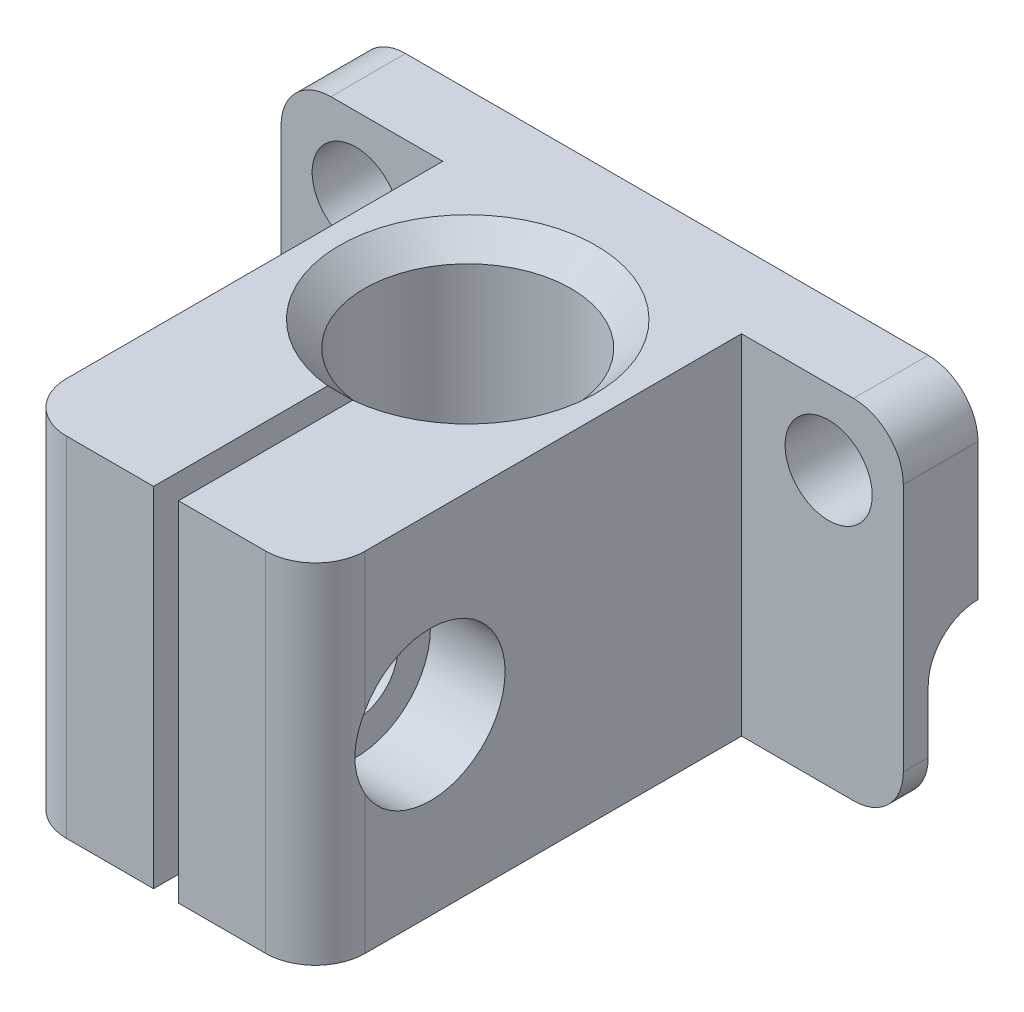
SolidWorks part; units mm, degrees
material "ABS"
ref_plane "Front Plane" through (0, 0, 0) normal (0, 0, 1) x (1, 0, 0)
ref_plane "Top Plane" through (0, 0, 0) normal (0, 1, 0) x (1, 0, 0)
ref_plane "Right Plane" through (0, 0, 0) normal (1, 0, 0) x (0, 0, -1)
sketch "Sketch1" plane through (0, 0, 0) normal (0, 1, 0) x (1, 0, 0)
  line L0 (-12.5, 0) -> (12.5, 0)
  line L1 (12.5, 0) -> (12.5, -3)
  line L2 (12.5, -3) -> (6, -3)
  line L3 (6, -3) -> (6, -20.1198)
  line L4 (6, -20.1198) -> (-6, -20.1198)
  line L5 (-6, -20.1198) -> (-6, -3)
  line L6 (-6, -3) -> (-12.5, -3)
  line L7 (-12.5, -3) -> (-12.5, 0)
  dimension "D1" = 25
  dimension "D2" = 3
  dimension "D3" = 12
  dimension "D4" = 20.1198
extrude "Boss-Extrude1" add sketch "Sketch1" along normal blind 14
sketch "Sketch2" plane through (0, 14, 0) normal (0, 1, 0) x (1, 0, 0)
  line L0 (-0.5, -12.1198) -> (-0.5, -20.1198)
  line L1 (0.5, -12.1198) -> (0.5, -20.1198)
  line L2 (-0.5, -20.1198) -> (0.5, -20.1198)
  line L4 (-6, -20.1198) -> (6, -20.1198) construction
  line L5 (12.5, 0) -> (-12.5, 0) construction
  arc A0 (0.5, -12.1198) -> (-0.5, -12.1198) centre (0, -8) ccw
  dimension "D1" = 1
  dimension "D2" = 8.3
  dimension "D3" = 8
extrude "Cut-Extrude1" cut sketch "Sketch2" against normal through all
chamfer "Chamfer1" distance 1 angle 45 2 edges at (0, 14, 3.85) (0, 0, 3.85)
fillet "Fillet1" radius 2 6 edges at (-12.5, 0, 1.5) (12.5, 0, 1.5) (12.5, 14, 1.5) (-12.5, 14, 1.5) (-6, 7, 20.1198) (6, 7, 20.1198)
sketch "Sketch3" plane through (0, 0, 3) normal (0, 0, 1) x (1, 0, 0)
  line L0 (-10.5, 14) -> (-6, 14) construction
  line L1 (-9.5, 11) -> (9.5, 11) construction
  line L2 (0, 11) -> (0, 14) construction
  line L3 (5.15, 14) -> (-5.15, 14) construction
  circle A0 centre (-9.5, 11) radius 1.75
  circle A1 centre (9.5, 11) radius 1.75
  dimension "D1" = 19
  dimension "D2" = 3
  dimension "D3" = 3.5
extrude "Cut-Extrude2" cut sketch "Sketch3" against normal through all
sketch "Sketch4" plane through (12.5, 0, 0) normal (1, 0, 0) x (0, 0, -1)
  line L0 (-2, 0) -> (-2, 4.5)
  line L1 (0, 12) -> (0, 2) construction
  line L2 (0, 6.5) -> (0, 0)
  line L3 (-2, 0) -> (0, 0)
  line L5 (-18.1198, 14) -> (-3, 14) construction
  arc A0 (-2, 4.5) -> (0, 6.5) centre (0, 4.5) cw
  circle A1 centre (-15.5, 7) radius 1.7
  dimension "D1" = 2
  dimension "D3" = 3.4
  dimension "D5" = 15.5
  dimension "D2" = 6.5
  dimension "D4" = 7
extrude "Cut-Extrude3" cut sketch "Sketch4" against normal through all
sketch "Sketch5" plane through (6, 0, 0) normal (1, 0, 0) x (0, 0, -1)
  circle A0 centre (-15.5, 7) radius 3
  dimension "D1" = 6
extrude "Cut-Extrude4" cut sketch "Sketch5" against normal blind 3
sketch "Sketch6" plane through (-6, 0, 0) normal (-1, 0, 0) x (0, 0, 1)
  line L1 (15.5, 3.5359) -> (18.5, 5.2679)
  line L2 (18.5, 5.2679) -> (18.5, 8.7321)
  line L3 (18.5, 8.7321) -> (15.5, 10.4641)
  line L4 (15.5, 10.4641) -> (12.5, 8.7321)
  line L5 (12.5, 8.7321) -> (12.5, 5.2679)
  line L6 (12.5, 5.2679) -> (15.5, 3.5359)
  circle A0 centre (15.5, 7) radius 3 construction
  dimension "D1" = 6
extrude "Cut-Extrude5" cut sketch "Sketch6" against normal blind 3
